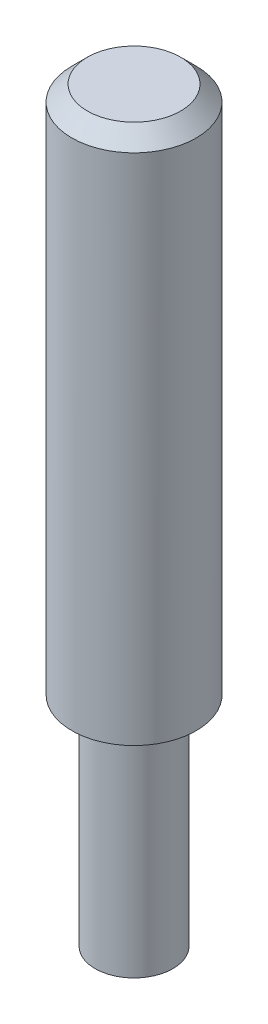
SolidWorks part; units mm, degrees
ref_plane "Front Plane" through (0, 0, 0) normal (0, 0, 1) x (1, 0, 0)
ref_plane "Top Plane" through (0, 0, 0) normal (0, 1, 0) x (1, 0, 0)
ref_plane "Right Plane" through (0, 0, 0) normal (1, 0, 0) x (0, 0, -1)
sketch "Sketch1" plane through (0, 0, 0) normal (0, 1, 0) x (1, 0, 0)
  circle A0 centre (0, 0) radius 4
extrude "Boss-Extrude1" add sketch "Sketch1" along normal blind 48
sketch "Sketch2" plane through (0, 0, 0) normal (0, -1, 0) x (1, 0, 0)
  circle A0 centre (0, 0) radius 4
  circle A1 centre (0, 0) radius 2.5
extrude "Cut-Extrude1" cut sketch "Sketch2" against normal blind 14
chamfer "Chamfer1" distance 1 angle 45 1 edges at (0, 48, 4)
